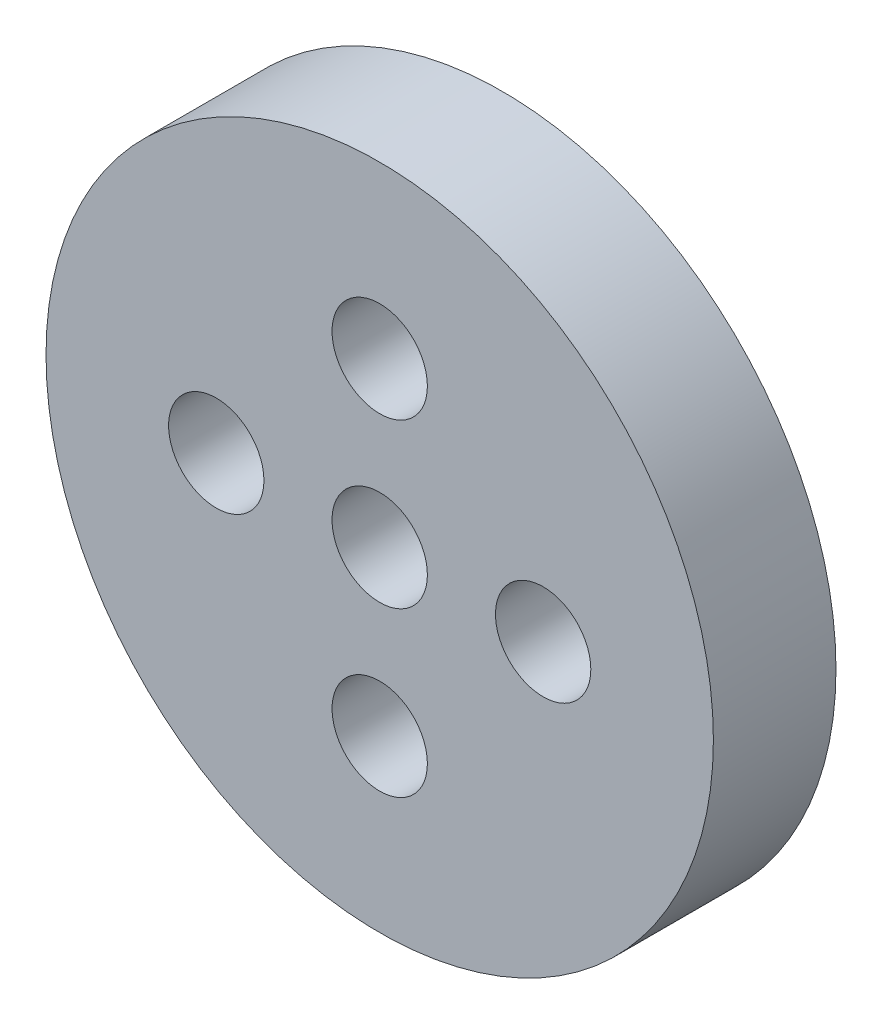
SolidWorks part; units mm, degrees
ref_plane "Plano frontal" through (0, 0, 0) normal (0, 0, 1) x (1, 0, 0)
ref_plane "Plano superior" through (0, 0, 0) normal (0, 1, 0) x (1, 0, 0)
ref_plane "Plano direito" through (0, 0, 0) normal (1, 0, 0) x (0, 0, -1)
sketch "Esboço1" plane through (0, 0, 0) normal (0, 0, 1) x (1, 0, 0)
  circle A0 centre (-21.9979, 9.4439) radius 24.5
  circle A1 centre (-33.9979, 9.4439) radius 3.5
  circle A2 centre (-21.9979, 21.4439) radius 3.5
  circle A3 centre (-9.9979, 9.4439) radius 3.5
  circle A4 centre (-21.9979, -2.5561) radius 3.5
  circle A5 centre (-21.9979, 9.4439) radius 3.5
  circle A6 centre (-21.9979, 9.4439) radius 18
  point P6 (0, 0)
  point P13 (-21.9979, 9.4439)
  dimension "D1" = 49
  dimension "D2" = 7
  dimension "D5" = 36
  dimension "D3" = 12
  dimension "D4" = 4
extrude "Ressalto-extrusão1" add sketch "Esboço1" along normal blind 9 contours A6 A1 A2 A3 A4 A5 | A0 A6
sketch "Esboço2" plane through (0, 0, 0) normal (0, 0, 1) x (1, 0, 0)
  circle A0 centre (-21.9979, 9.4439) radius 18
  dimension "D1" = 36
extrude "Corte-extrusão1" cut sketch "Esboço2" along normal blind 2 draft 45
